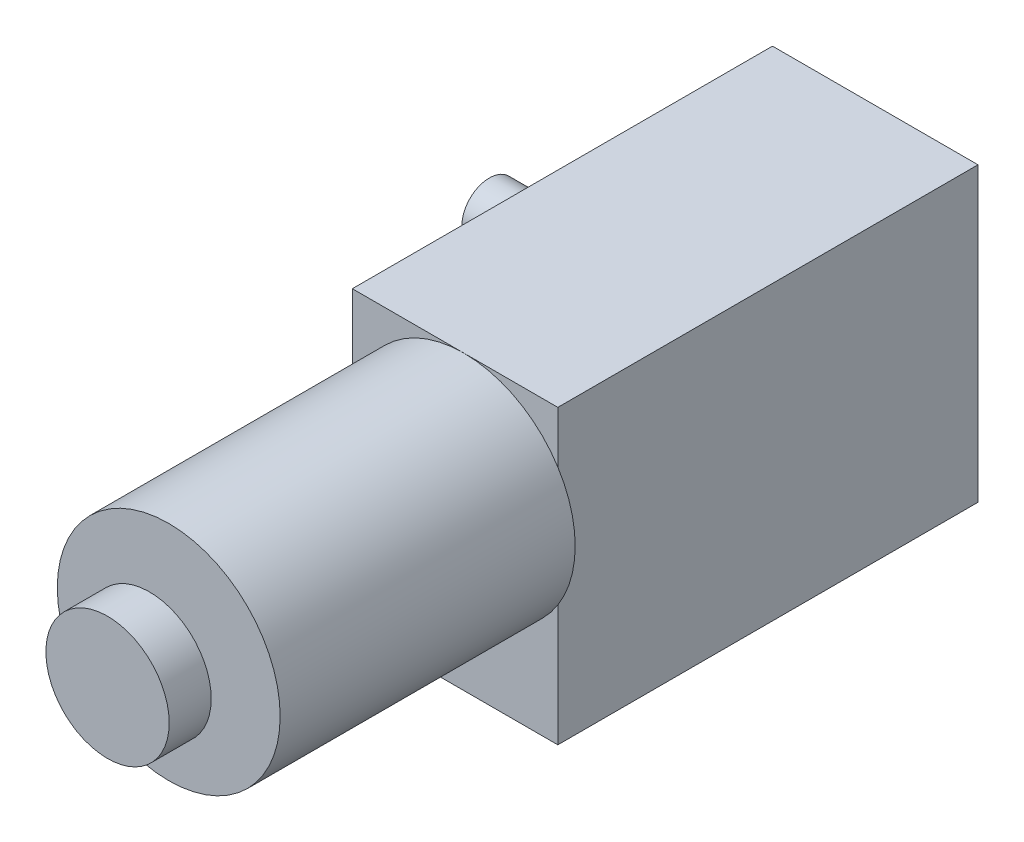
SolidWorks part; units mm, degrees
ref_plane "前视基准面" through (0, 0, 0) normal (0, 0, 1) x (1, 0, 0)
ref_plane "上视基准面" through (0, 0, 0) normal (0, 1, 0) x (1, 0, 0)
ref_plane "右视基准面" through (0, 0, 0) normal (1, 0, 0) x (0, 0, -1)
sketch "Sketch1" plane through (0, 0, 0) normal (0, 0, 1) x (1, 0, 0)
  circle A0 centre (0, 0) radius 12.2
  dimension "D1" = 24.4
extrude "Extrude1" add sketch "Sketch1" along normal blind 32.3
sketch "Sketch2" plane through (0, 0, 32.3) normal (0, 0, 1) x (1, 0, 0)
  circle A0 centre (0, 0) radius 2.05
  dimension "D1" = 4.1
extrude "Extrude2" add sketch "Sketch2" along normal blind 2.1
sketch "Sketch3" plane through (0, 0, 34.4) normal (0, 0, 1) x (1, 0, 0)
  circle A0 centre (0, 0) radius 6.75
  dimension "D1" = 13.5
extrude "Extrude3" add sketch "Sketch3" along normal blind 4.6
sketch "Sketch4" plane through (0, 0, 0) normal (0, 0, -1) x (-1, 0, 0)
  line L1 (12.2, 12.2) -> (-10.3, 12.2)
  line L2 (12.2, 12.2) -> (12.2, -19.8)
  line L3 (12.2, -19.8) -> (-10.3, -19.8)
  line L4 (-10.3, 12.2) -> (-10.3, -19.8)
  circle A0 centre (0, 0) radius 12.2 construction
  dimension "D1" = 22.5
  dimension "D2" = 32
extrude "Extrude4" add sketch "Sketch4" along normal blind 46
sketch "Sketch5" plane through (-12.2, 0, 0) normal (-1, 0, 0) x (0, 0, 1)
  line L0 (-46, -3.8) -> (0, -3.8) construction
  line L1 (-46, -19.8) -> (-46, 12.2) construction
  line L2 (0, -19.8) -> (0, 0) construction
  line L3 (-23.5, 12.2) -> (-23.5, -19.8) construction
  line L6 (-18.5, -8.8) -> (-18.5, 1.2) construction
  line L7 (-20, -8.8) -> (-20, 1.2)
  line L8 (-17, -8.8) -> (-17, 1.2)
  circle A0 centre (-40, -12.8) radius 3.7
  circle A1 centre (-40, -12.8) radius 1.5
  circle A2 centre (-40, 5.2) radius 1.5
  circle A3 centre (-40, 5.2) radius 3.7
  circle A4 centre (-7, 5.2) radius 3.7
  circle A5 centre (-7, 5.2) radius 1.5
  circle A6 centre (-7, -12.8) radius 1.5
  circle A7 centre (-7, -12.8) radius 3.7
  circle A8 centre (-31, -3.8) radius 6.5
  arc A9 (-20, -8.8) -> (-17, -8.8) centre (-18.5, -8.8) ccw
  arc A10 (-17, 1.2) -> (-20, 1.2) centre (-18.5, 1.2) ccw
  point P24 (-18.5, -3.8)
  dimension "D5" = 3
  dimension "D6" = 7.4
  dimension "D7" = 13
  dimension "D1" = 33
  dimension "D2" = 18
  dimension "D3" = 15
  dimension "D4" = 9
  dimension "D8" = 10
  dimension "D9" = 3
  dimension "D10" = 5
extrude "Extrude5" add sketch "Sketch5" along normal blind 2
sketch "Sketch6" plane through (-14.2, 0, 0) normal (-1, 0, 0) x (0, 0, 1)
  circle A0 centre (-31, -3.8) radius 3
  dimension "D1" = 6
extrude "Extrude6" add sketch "Sketch6" along normal blind 14
sketch "Sketch7" plane through (-28.2, 0, 0) normal (-1, 0, 0) x (0, 0, 1)
  circle A0 centre (-31, -3.8) radius 1.5
  dimension "D1" = 3
extrude "Extrude7" cut sketch "Sketch7" against normal blind 8
